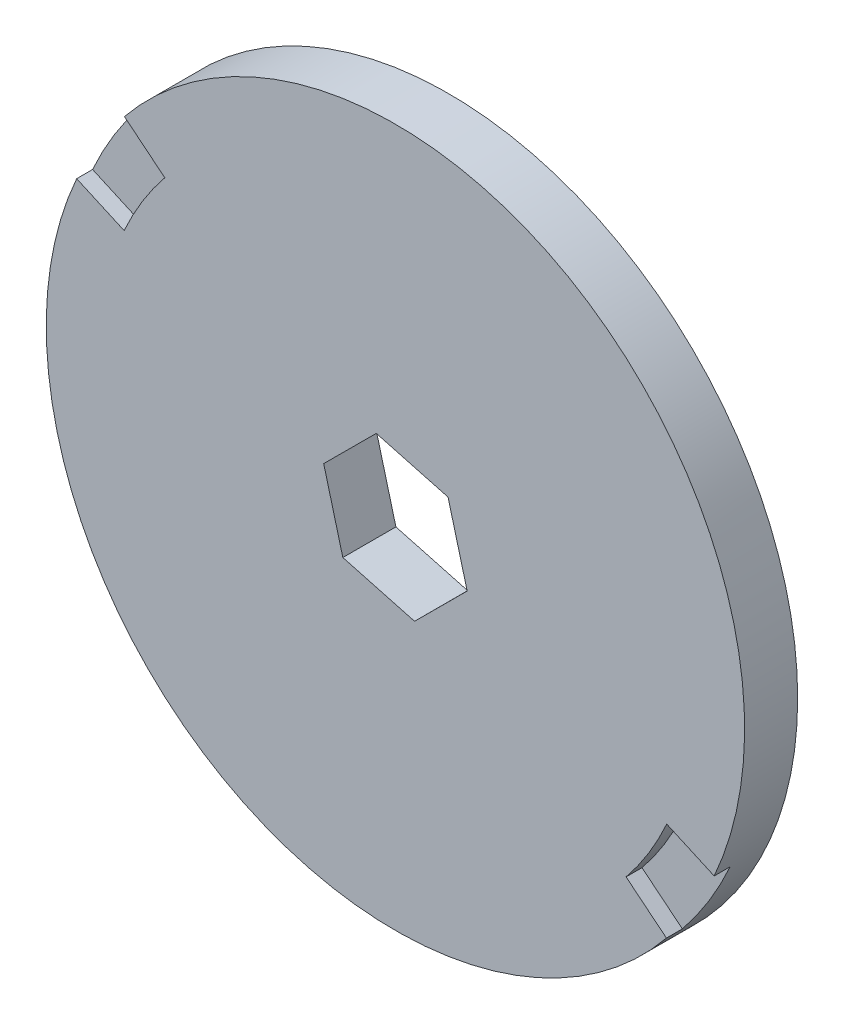
SolidWorks part; units mm, degrees
ref_plane "前视基准面" through (0, 0, 0) normal (0, 0, 1) x (1, 0, 0)
ref_plane "上视基准面" through (0, 0, 0) normal (0, 1, 0) x (1, 0, 0)
ref_plane "右视基准面" through (0, 0, 0) normal (1, 0, 0) x (0, 0, -1)
other "Configuration Table"
sketch "草图1" plane through (0, 0, 0) normal (0, 0, 1) x (1, 0, 0)
  line L1 (6.7592, -1.8203) -> (4.956, 4.9435)
  line L2 (4.956, 4.9435) -> (-1.8032, 6.7638)
  line L3 (-1.8032, 6.7638) -> (-6.7592, 1.8203)
  line L4 (-6.7592, 1.8203) -> (-4.956, -4.9435)
  line L5 (-4.956, -4.9435) -> (1.8032, -6.7638)
  line L6 (1.8032, -6.7638) -> (6.7592, -1.8203)
  circle A0 centre (0, 0) radius 32.9
  circle A1 centre (0, 0) radius 6.0622 construction
  dimension "D1" = 65.8
  dimension "D2" = 14
extrude "凸台-拉伸1" add sketch "草图1" along normal blind 5
sketch "草图2" plane through (0, 0, 5) normal (0, 0, 1) x (1, 0, 0)
  line L0 (-30.0329, 13.4326) -> (-25.5599, 11.432)
  line L1 (-21.7302, 17.6578) -> (-25.533, 20.748)
  arc A0 (-30.0329, 13.4326) -> (-25.533, 20.748) centre (0, 0) cw
  circle A1 centre (0, 0) radius 32.9 construction
  arc A2 (-25.5599, 11.432) -> (-21.7302, 17.6578) centre (0, 0) cw
  dimension "D2" = 28
  dimension "D1" = 15
extrude "切除-拉伸1" cut sketch "草图2" against normal blind 1.5
pattern_circular "阵列(圆周)1" count 2 over 360 about axis through (0, 0, 0) along (0, 0, 1) of "切除-拉伸1"
